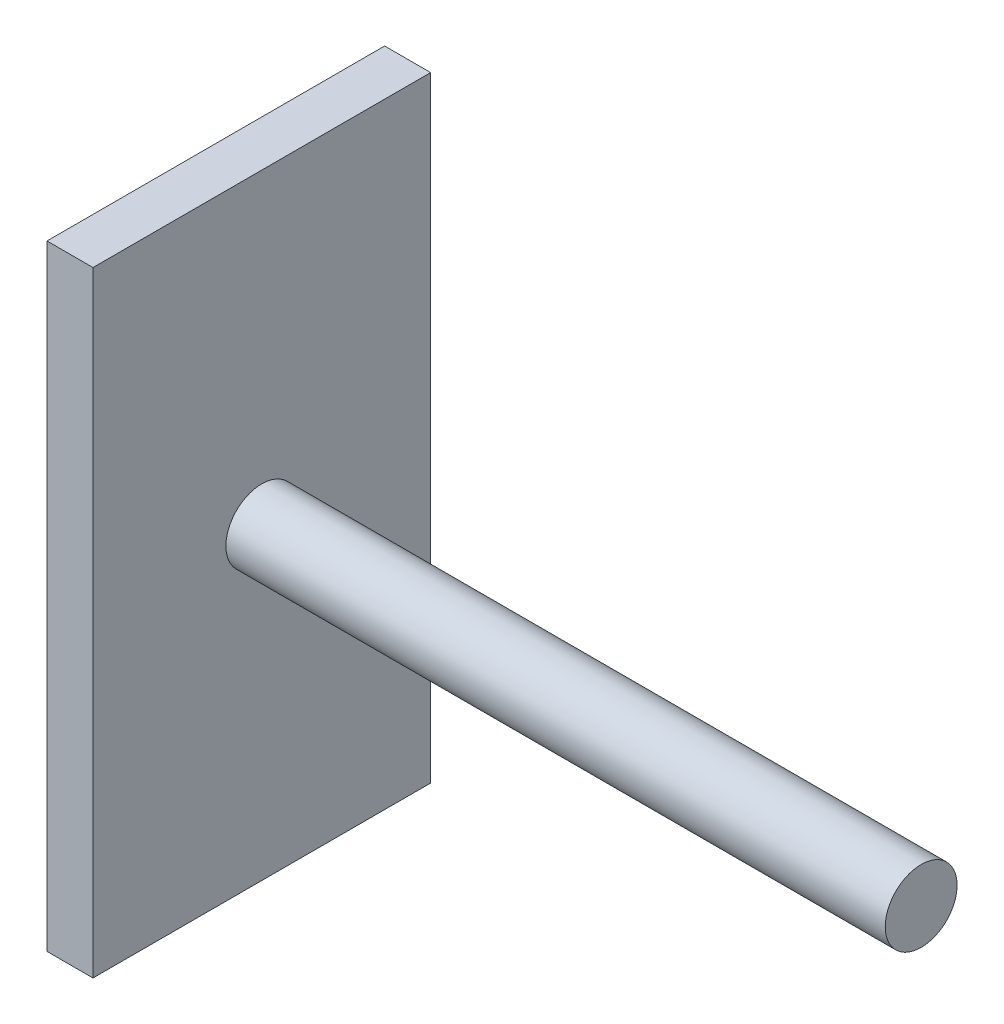
SolidWorks part; units mm, degrees
ref_plane "Plan de face" through (0, 0, 0) normal (0, 0, 1) x (1, 0, 0)
ref_plane "Plan de dessus" through (0, 0, 0) normal (0, 1, 0) x (1, 0, 0)
ref_plane "Plan de droite" through (0, 0, 0) normal (1, 0, 0) x (0, 0, -1)
sketch "Esquisse1" plane through (0, 0, 0) normal (1, 0, 0) x (0, 0, -1)
  line L0 (0, 0) -> (0, 25)
  line L1 (0, 0) -> (13.72, 0)
  line L2 (13.72, 0) -> (13.72, 25)
  line L3 (13.72, 25) -> (0, 25)
extrude "Boss.-Extru.1" add sketch "Esquisse1" along normal blind 1.87 contours L3 L0 L1 L2
sketch "Esquisse2" plane through (1.87, 0, 0) normal (1, 0, 0) x (0, 0, -1)
  circle A0 centre (6.86, 12.5) radius 1.46
extrude "Boss.-Extru.2" add sketch "Esquisse2" along normal blind 26.79
